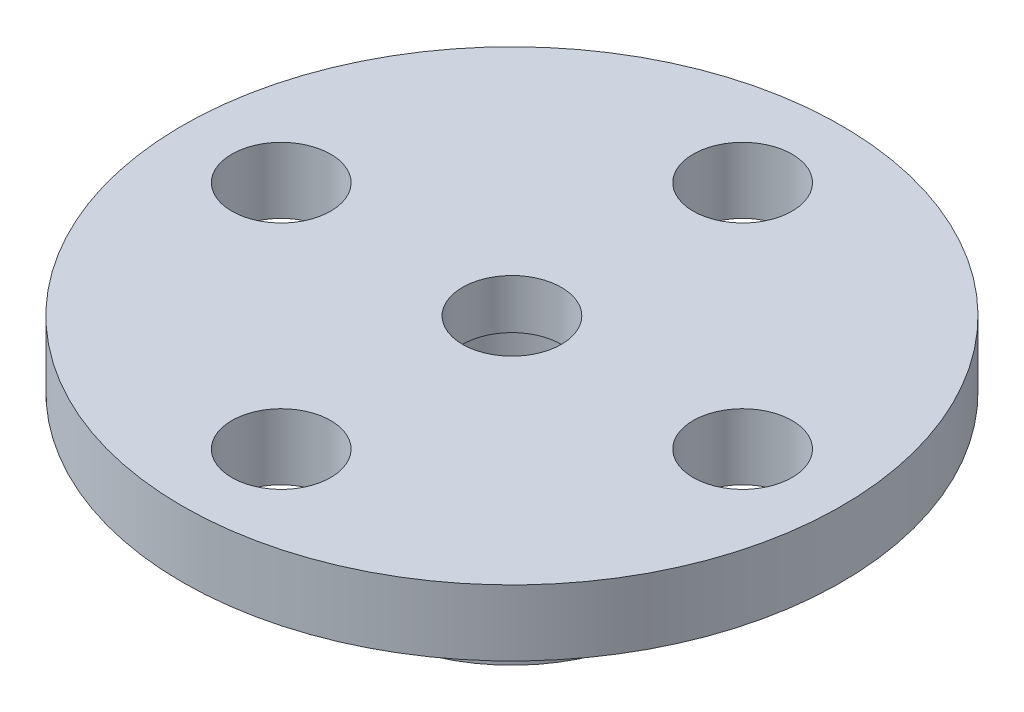
SolidWorks part; units mm, degrees
material "氧化铝"
ref_plane "前视基准面" through (0, 0, 0) normal (0, 0, 1) x (1, 0, 0)
ref_plane "上视基准面" through (0, 0, 0) normal (0, 1, 0) x (1, 0, 0)
ref_plane "右视基准面" through (0, 0, 0) normal (1, 0, 0) x (0, 0, -1)
other "Configuration Table"
sketch "草图1" plane through (0, 0, 0) normal (0, 1, 0) x (1, 0, 0)
  line L0 (0, 16.2329) -> (0, -15.9118) construction
  line L1 (0, 0) -> (0, 7) construction
  circle A0 centre (0, 0) radius 10
  circle A1 centre (0, 0) radius 7 construction
  circle A2 centre (0, 7) radius 1.5
  circle A3 centre (7, 0) radius 1.5
  circle A4 centre (0, -7) radius 1.5
  circle A5 centre (-7, 0) radius 1.5
  dimension "D1" = 20
  dimension "D2" = 14
  dimension "D3" = 3
  dimension "D5" = 7
  dimension "D4" = 4
extrude "凸台-拉伸1" add sketch "草图1" along normal blind 2
sketch "草图2" plane through (0, 0, 0) normal (0, 1, 0) x (1, 0, 0)
  circle A0 centre (0, 0) radius 4.5
  dimension "D1" = 9
extrude "凸台-拉伸2" add sketch "草图2" against normal blind 4
sketch "草图3" plane through (0, 0, 0) normal (0, 1, 0) x (1, 0, 0)
  circle A0 centre (0, 0) radius 1.5
  dimension "D1" = 3
extrude "切除-拉伸1" cut sketch "草图3" against normal through all both and the other way through all
sketch "草图4" plane through (0, 0, 0) normal (0, 1, 0) x (1, 0, 0)
  circle A0 centre (0, 0) radius 2.45
  dimension "D1" = 4.9
extrude "切除-拉伸2" cut sketch "草图4" along normal blind 4.5 from surface at -4 starting at face at (0, -4, 1.5)
